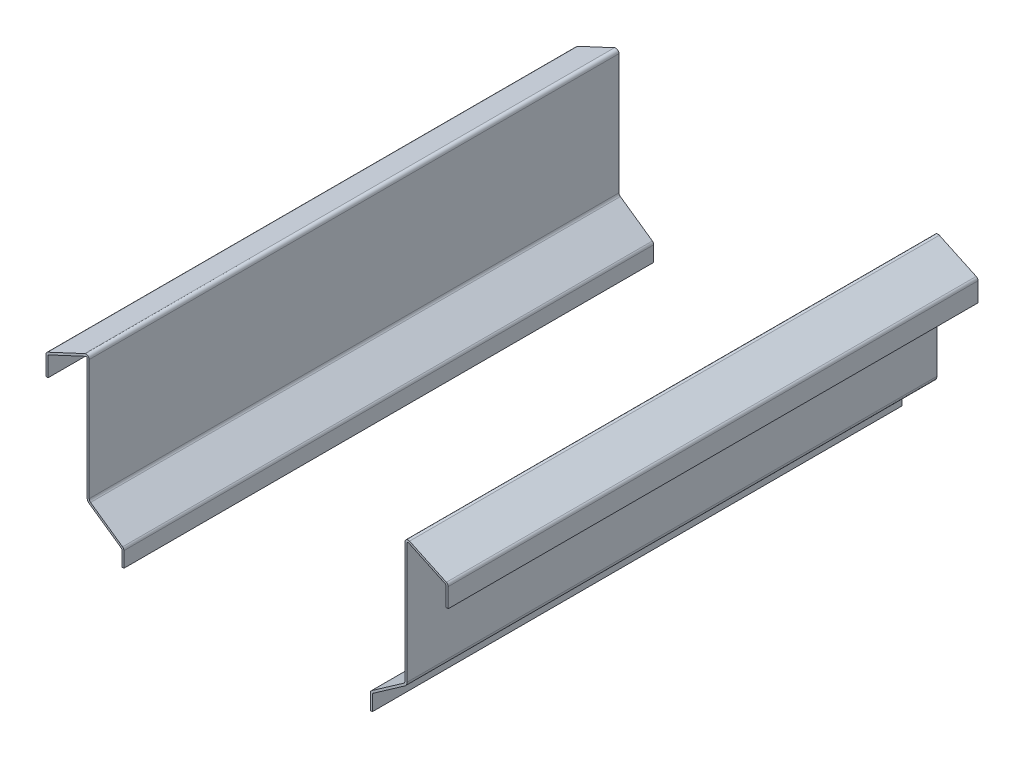
SolidWorks part; units mm, degrees
material "AISI 1015 Steel, Cold Drawn (SS)"
ref_plane "Front Plane" through (0, 0, 0) normal (0, 0, 1) x (1, 0, 0)
ref_plane "Top Plane" through (0, 0, 0) normal (0, 1, 0) x (1, 0, 0)
ref_plane "Right Plane" through (0, 0, 0) normal (1, 0, 0) x (0, 0, -1)
sketch "Sketch1" plane through (0, 0, 0) normal (0, 0, 1) x (1, 0, 0)
  line L12 (149, 0) -> (-149, 0)
  line L25 (-118.2339, -26.0665) -> (-118.2339, -40.5048)
  line L51 (-118.2339, -40.5048) -> (-116.2339, -40.5048)
  line L52 (-116.2339, -40.5048) -> (-116.2339, -26.0665)
  line L53 (-117.5132, -23.609) -> (-147.7207, -2.4575)
  line L54 (-149, 0) -> (-149, 113.7292)
  line L55 (-153.2679, 116.4482) -> (-188.0517, 100.2282)
  line L56 (-189.7839, 97.5093) -> (-189.7839, 79.4205)
  line L57 (-189.7839, 79.4205) -> (-187.7839, 79.4205)
  line L58 (-187.7839, 79.4205) -> (-187.7839, 97.5093)
  line L59 (-187.2065, 98.4156) -> (-152.4226, 114.6355)
  line L60 (-151, 113.7292) -> (-151, 0)
  line L61 (-148.8679, -4.0958) -> (-118.6603, -25.2473)
  line L62 (0, -141.1385) -> (0, 141.1385) construction
  line L63 (148.8679, -4.0958) -> (118.6603, -25.2473)
  line L64 (151, 113.7292) -> (151, 0)
  line L65 (187.2065, 98.4156) -> (152.4226, 114.6355)
  line L66 (187.7839, 79.4205) -> (187.7839, 97.5093)
  line L67 (189.7839, 79.4205) -> (187.7839, 79.4205)
  line L68 (189.7839, 97.5093) -> (189.7839, 79.4205)
  line L69 (153.2679, 116.4482) -> (188.0517, 100.2282)
  line L70 (149, 0) -> (149, 113.7292)
  line L71 (117.5132, -23.609) -> (147.7207, -2.4575)
  line L72 (116.2339, -40.5048) -> (116.2339, -26.0665)
  line L73 (118.2339, -40.5048) -> (116.2339, -40.5048)
  line L74 (118.2339, -26.0665) -> (118.2339, -40.5048)
  arc A32 (-116.2339, -26.0665) -> (-117.5132, -23.609) centre (-119.2339, -26.0665) ccw
  arc A33 (-149, 0) -> (-147.7207, -2.4575) centre (-146, 0) ccw
  arc A34 (-149, 113.7292) -> (-153.2679, 116.4482) centre (-152, 113.7292) ccw
  arc A35 (-188.0517, 100.2282) -> (-189.7839, 97.5093) centre (-186.7839, 97.5093) ccw
  arc A36 (-187.2065, 98.4156) -> (-187.7839, 97.5093) centre (-186.7839, 97.5093) ccw
  arc A37 (-151, 113.7292) -> (-152.4226, 114.6355) centre (-152, 113.7292) ccw
  arc A38 (-151, 0) -> (-148.8679, -4.0958) centre (-146, 0) ccw
  arc A39 (-118.2339, -26.0665) -> (-118.6603, -25.2473) centre (-119.2339, -26.0665) ccw
  arc A40 (118.2339, -26.0665) -> (118.6603, -25.2473) centre (119.2339, -26.0665) cw
  arc A41 (151, 0) -> (148.8679, -4.0958) centre (146, 0) cw
  arc A42 (151, 113.7292) -> (152.4226, 114.6355) centre (152, 113.7292) cw
  arc A43 (187.2065, 98.4156) -> (187.7839, 97.5093) centre (186.7839, 97.5093) cw
  arc A44 (188.0517, 100.2282) -> (189.7839, 97.5093) centre (186.7839, 97.5093) cw
  arc A45 (149, 113.7292) -> (153.2679, 116.4482) centre (152, 113.7292) cw
  arc A46 (149, 0) -> (147.7207, -2.4575) centre (146, 0) cw
  arc A47 (116.2339, -26.0665) -> (117.5132, -23.609) centre (119.2339, -26.0665) cw
  point P28 (0, 0)
  dimension "D2" = 3
  dimension "D3" = 1
  dimension "D4" = 116.2339
  dimension "D1" = 149
  dimension "D5" = 117.5132
  dimension "D6" = 152.4226
  dimension "D7" = 186.7839
  dimension "D8" = 79.4205
  dimension "D9" = 97.5093
  dimension "D10" = 40.5048
extrude "Boss-Extrude1" add sketch "Sketch1" along normal blind 500 contours A39 L25 L51 L52 A32 L53 A33 L54 A34 L55 A35 L56 L57 L58 A36 L59 A37 L60 A38 L61 | A47 L72 L73 L74 A40 L63 A41 L64 A42 L65 A43 L66 L67 L68 A44 L69 A45 L70 A46 L71
sketch "Sketch2" plane through (-151, 0, 0) normal (-1, 0, 0) x (0, 0, 1)
  line L0 (500, 0) -> (0, 0) construction
  line L1 (435, 113.7292) -> (500, 113.7292)
  line L2 (435, 113.7292) -> (435, 0)
  line L3 (435, 0) -> (500, 0)
  line L4 (500, 113.7292) -> (500, 0)
  line L5 (435, 113.7292) -> (500, 0) construction
  line L6 (435, 0) -> (500, 113.7292) construction
  line L7 (500, 113.7292) -> (0, 113.7292) construction
  line L8 (500, 113.7292) -> (500, 0) construction
  point P0 (467.5, 56.8646)
  dimension "D1" = 32.5
